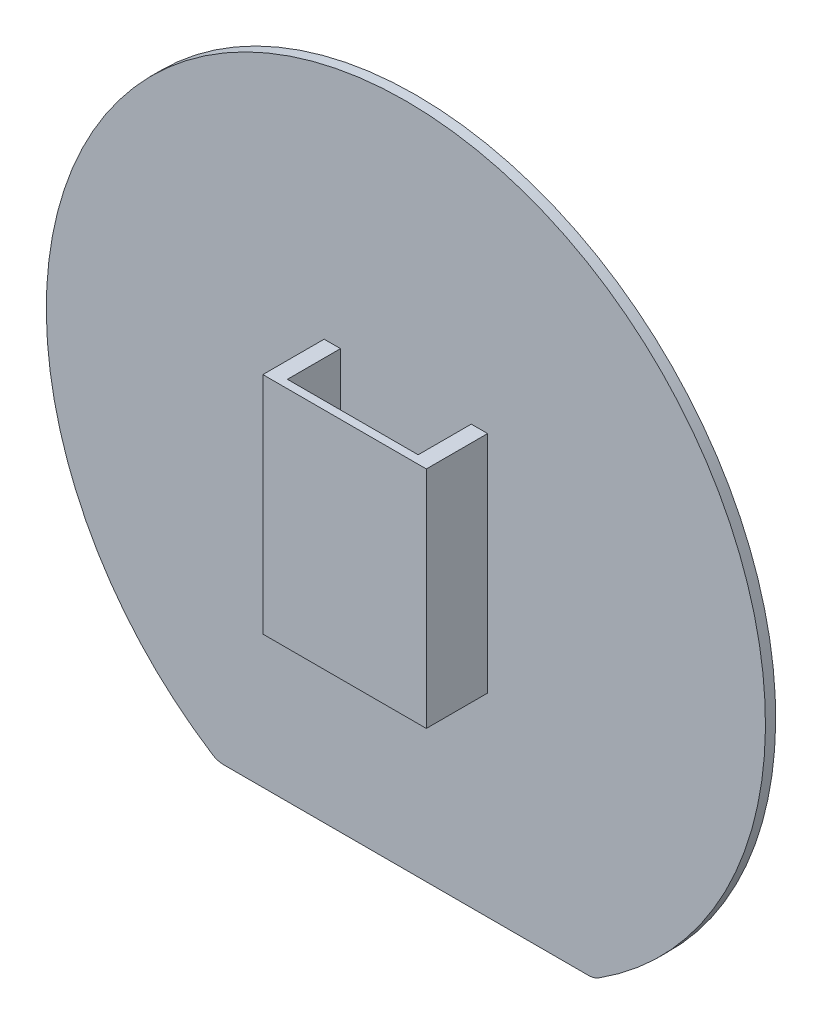
SolidWorks part; units mm, degrees
ref_plane "Front Plane" through (0, 0, 0) normal (0, 0, 1) x (1, 0, 0)
ref_plane "Top Plane" through (0, 0, 0) normal (0, 1, 0) x (1, 0, 0)
ref_plane "Right Plane" through (0, 0, 0) normal (1, 0, 0) x (0, 0, -1)
sketch "Sketch1" plane through (0, 0, 0) normal (0, 0, 1) x (1, 0, 0)
  line L0 (0, 109.2621) -> (0, -96.9942) construction
  line L1 (-109.4364, 0) -> (110.4876, 0) construction
  line L2 (0, 0) -> (62.2254, 62.2254) construction
  line L3 (0, 0) -> (76.2102, -44) construction
  line L4 (0, 0) -> (-62.2254, 62.2254) construction
  line L5 (0, 0) -> (-76.2102, -44) construction
  line L6 (-46.0326, -75) -> (46.0326, -75)
  circle A0 centre (0, 0) radius 88 construction
  circle A1 centre (0, 0) radius 88
  dimension "D1" = 176
  dimension "D6" = 75
  dimension "D2" = 45
  dimension "D3" = 45
  dimension "D4" = 60
  dimension "D5" = 60
extrude "Boss-Extrude1" add sketch "Sketch1" against normal blind 2.5 contours L6 A1
sketch "Sketch2" plane through (0, 0, 0) normal (0, 0, 1) x (1, 0, 0)
  line L1 (-20, -27.5) -> (20, -27.5)
  line L2 (-20, -27.5) -> (-20, 27.5)
  line L3 (-20, 27.5) -> (20, 27.5)
  line L4 (20, -27.5) -> (20, 27.5)
  line L5 (-20, -27.5) -> (20, 27.5) construction
  line L6 (-20, 27.5) -> (20, -27.5) construction
  point P0 (0, 0)
  dimension "D1" = 40
  dimension "D2" = 55
extrude "Boss-Extrude2" add sketch "Sketch2" along normal blind 15
sketch "Sketch3" plane through (0, -27.5, 0) normal (0, -1, 0) x (1, 0, 0)
  line L0 (-20, 0) -> (20, 0) construction
  line L1 (-16, 0) -> (16, 0)
  line L2 (-16, 0) -> (-16, 13)
  line L3 (-16, 13) -> (16, 13)
  line L4 (16, 0) -> (16, 13)
  line L5 (-20, 15) -> (20, 15) construction
  point P7 (0, 13)
  dimension "D1" = 32
  dimension "D2" = 2
extrude "Cut-Extrude1" cut sketch "Sketch3" against normal through all
fillet "Fillet1" radius 5 2 edges at (46.0326, -75, -1.25) (-46.0326, -75, -1.25)
